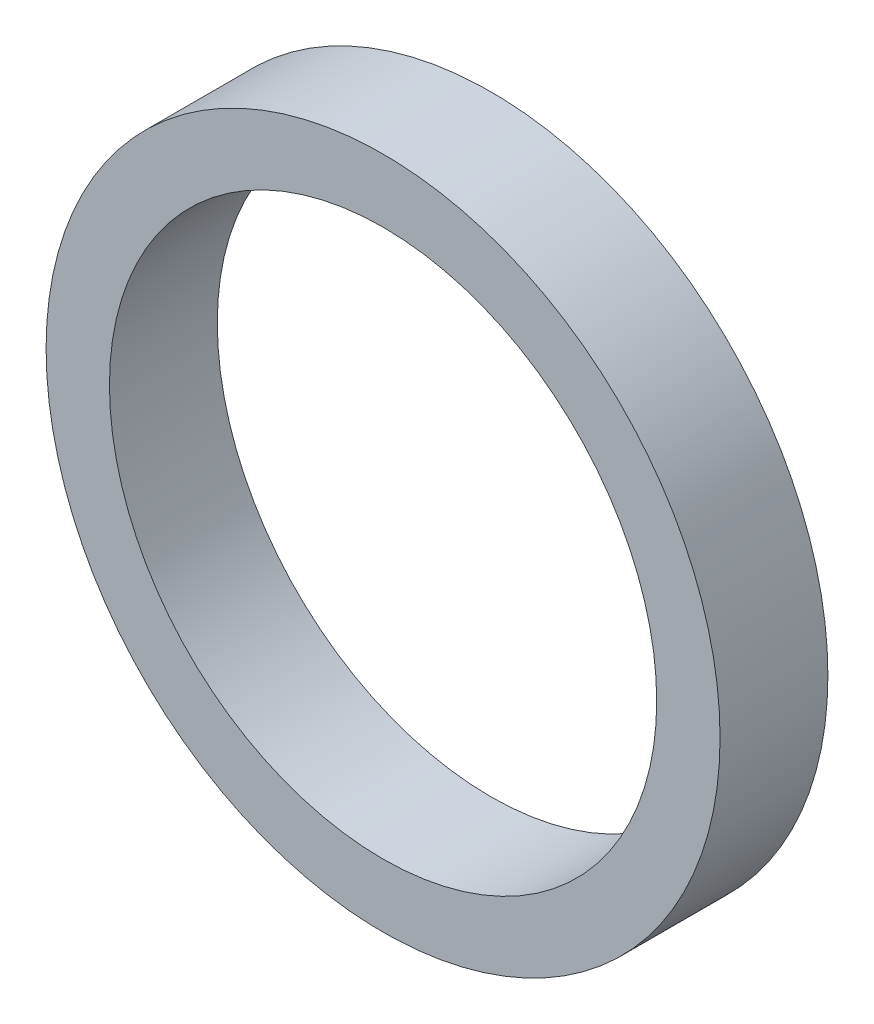
SolidWorks part; units mm, degrees
ref_plane "前视基准面" through (0, 0, 0) normal (0, 0, 1) x (1, 0, 0)
ref_plane "上视基准面" through (0, 0, 0) normal (0, 1, 0) x (1, 0, 0)
ref_plane "右视基准面" through (0, 0, 0) normal (1, 0, 0) x (0, 0, -1)
other "Configuration Table"
sketch "草图1" plane through (0, 0, 0) normal (0, 0, 1) x (1, 0, 0)
  circle A0 centre (0, 0) radius 10.15
  circle A1 centre (0, 0) radius 12.5
  dimension "D1" = 20.3
  dimension "D2" = 25
extrude "凸台-拉伸1" add sketch "草图1" along normal blind 4
